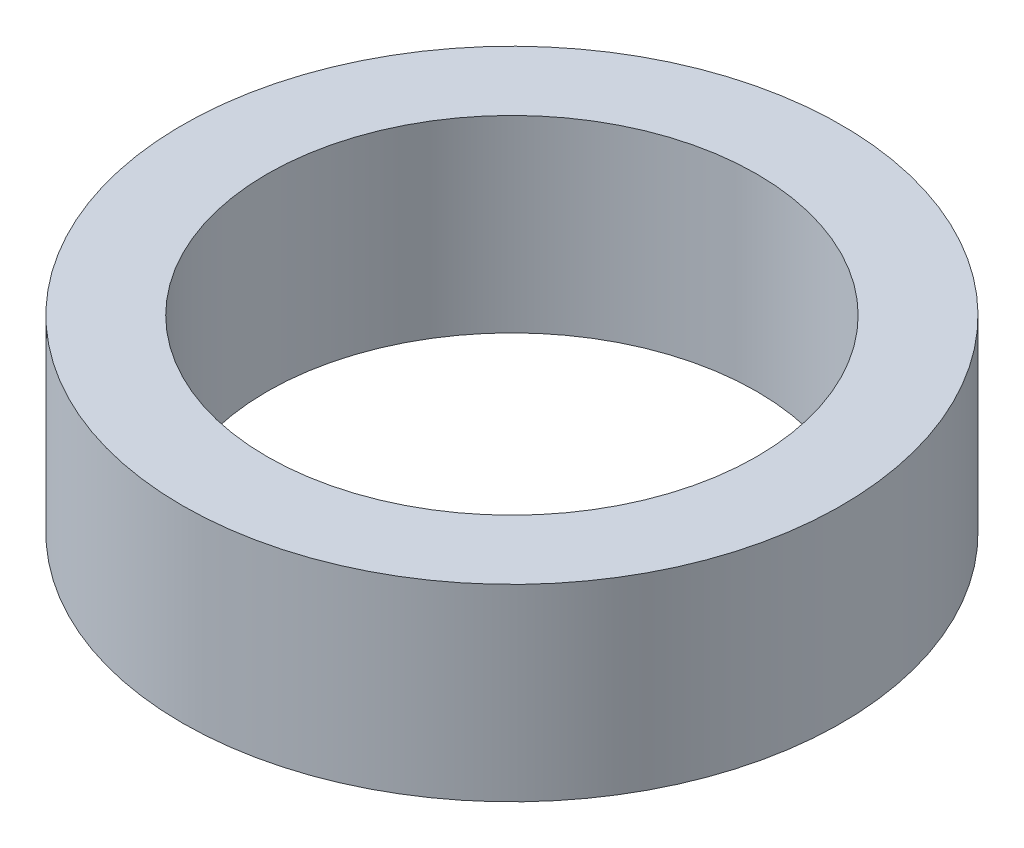
SolidWorks part; units mm, degrees
ref_plane "Front Plane" through (0, 0, 0) normal (0, 0, 1) x (1, 0, 0)
ref_plane "Top Plane" through (0, 0, 0) normal (0, 1, 0) x (1, 0, 0)
ref_plane "Right Plane" through (0, 0, 0) normal (1, 0, 0) x (0, 0, -1)
sketch "Sketch1" plane through (0, 0, 0) normal (0, 1, 0) x (1, 0, 0)
  circle A0 centre (0, 0) radius 3.5
  circle A1 centre (0, 0) radius 2.6
  dimension "D1" = 5.2
  dimension "D2" = 7
extrude "Boss-Extrude1" add sketch "Sketch1" along normal blind 2
